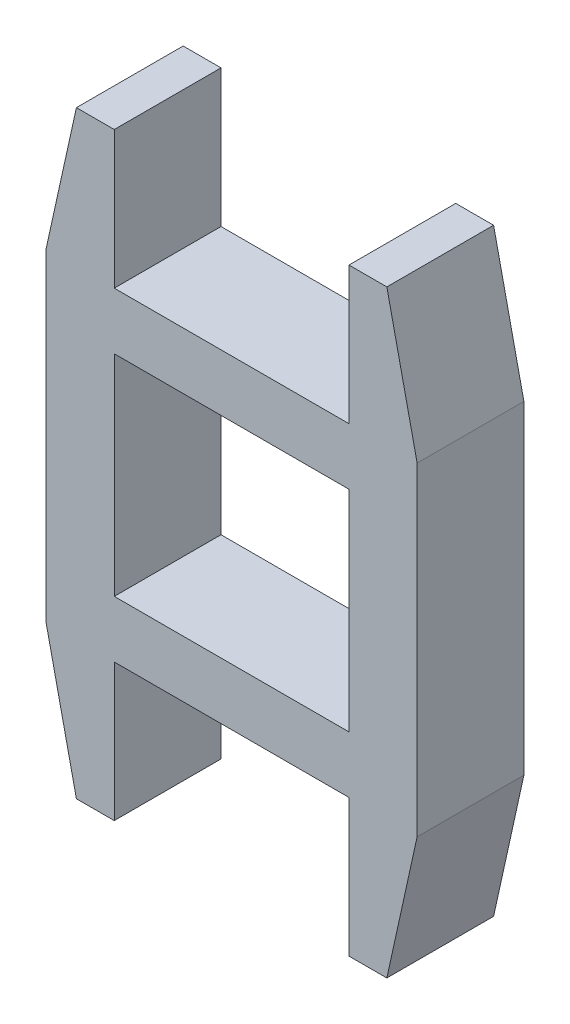
SolidWorks part; units mm, degrees
material "Acrylic (Medium-high impact)"
ref_plane "Front Plane" through (0, 0, 0) normal (0, 0, 1) x (1, 0, 0)
ref_plane "Top Plane" through (0, 0, 0) normal (0, 1, 0) x (1, 0, 0)
ref_plane "Right Plane" through (0, 0, 0) normal (1, 0, 0) x (0, 0, -1)
sketch "Sketch1" plane through (0, 0, 0) normal (0, 0, 1) x (1, 0, 0)
  line L0 (1247.2096, 961.4272) -> (1247.2096, 950.3272)
  line L1 (1263.2096, 948.7853) -> (1243.6096, 948.7853) construction
  line L2 (1247.2096, 947.3272) -> (1243.6096, 947.3272) construction
  line L3 (1247.2096, 961.4272) -> (1259.6096, 961.4272)
  line L4 (1245.2096, 971.6864) -> (1247.2096, 971.6864)
  line L5 (1247.2096, 971.6864) -> (1247.2096, 964.4272)
  line L6 (1247.2096, 955.8772) -> (1259.6096, 955.8772) construction
  line L7 (1259.6096, 964.4272) -> (1247.2096, 964.4272)
  line L8 (1243.6096, 964.4272) -> (1243.6096, 947.3272)
  line L9 (1243.6096, 947.3272) -> (1245.2096, 940.068)
  line L10 (1247.2096, 964.4272) -> (1243.6096, 964.4272) construction
  line L11 (1259.6096, 947.3272) -> (1247.2096, 947.3272)
  line L12 (1243.6096, 964.4272) -> (1245.2096, 971.6864)
  line L13 (1247.2096, 940.068) -> (1247.2096, 947.3272)
  line L14 (1245.2096, 940.068) -> (1247.2096, 940.068)
  line L15 (1247.2096, 950.3272) -> (1259.6096, 950.3272)
  line L16 (1259.6096, 964.4272) -> (1263.2096, 964.4272) construction
  line L17 (1259.6096, 947.3272) -> (1263.2096, 947.3272) construction
  line L18 (1261.6096, 940.068) -> (1259.6096, 940.068)
  line L19 (1253.4096, -38.8351) -> (1253.4096, 49961.1649) construction
  line L20 (1259.6096, 940.068) -> (1259.6096, 947.3272)
  line L21 (1263.2096, 964.4272) -> (1261.6096, 971.6864)
  line L22 (1263.2096, 947.3272) -> (1261.6096, 940.068)
  line L23 (1263.2096, 964.4272) -> (1263.2096, 947.3272)
  line L24 (1259.6096, 971.6864) -> (1259.6096, 964.4272)
  line L25 (1261.6096, 971.6864) -> (1259.6096, 971.6864)
  line L26 (1263.2096, 962.9691) -> (1243.6096, 962.9691) construction
  line L27 (1259.6096, 961.4272) -> (1259.6096, 950.3272)
  point P2 (1263.2096, 955.8772)
  point P14 (1243.6096, 955.8772)
  point P15 (1253.4096, 964.4272)
  point P20 (1253.4096, 962.9691)
  point P26 (1253.4096, 955.8772)
  point P28 (1253.4096, 964.4272)
  point P30 (1253.4096, 961.4272)
  point P31 (1253.4096, 948.7853)
  point P33 (1253.4096, 950.3272)
  point P36 (1253.4096, 947.3272)
  point P38 (1253.4096, 961.4272)
  dimension "D1" = 6.2
  dimension "D2" = 7.2592
  dimension "D3" = 2
  dimension "D4" = 3
  dimension "D5" = 8.55
  dimension "D8" = 3.6
extrude "Boss-Extrude1" add sketch "Sketch1" along normal blind 5.64
